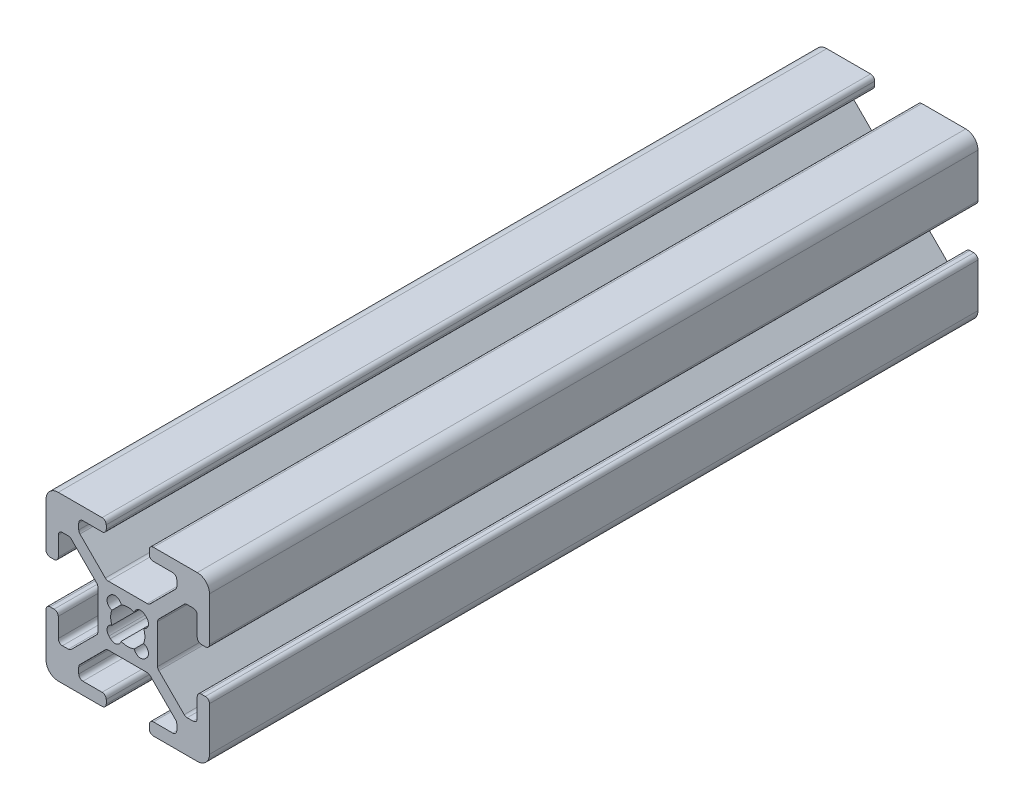
SolidWorks part; units mm, degrees
material "1060 Alloy"
ref_plane "Front Plane" through (0, 0, 0) normal (0, 0, 1) x (1, 0, 0)
ref_plane "Top Plane" through (0, 0, 0) normal (0, 1, 0) x (1, 0, 0)
ref_plane "Right Plane" through (0, 0, 0) normal (1, 0, 0) x (0, 0, -1)
sketch "Sketch2" plane through (0, 0, 0) normal (0, 0, 1) x (1, 0, 0)
  line L0 (-10, -3.138) -> (-10, -8.5)
  line L1 (-8.5, -10) -> (-3.138, -10)
  line L2 (-2.63, -9.492) -> (-2.63, -9.008)
  line L3 (-3.138, -8.5) -> (-5.487, -8.5)
  line L4 (-5.995, -7.992) -> (-5.995, -7.2662)
  line L5 (-5.8462, -6.907) -> (-2.743, -3.8038)
  line L6 (-2.3838, -3.655) -> (2.3841, -3.655)
  line L7 (2.7433, -3.8038) -> (5.8462, -6.9067)
  line L8 (5.995, -7.2659) -> (5.995, -7.992)
  line L9 (5.487, -8.5) -> (3.138, -8.5)
  line L10 (2.63, -9.008) -> (2.63, -9.492)
  line L11 (3.138, -10) -> (8.5, -10)
  line L12 (10, -8.5) -> (10, -3.138)
  line L13 (9.492, -2.63) -> (9.008, -2.63)
  line L14 (8.5, -3.138) -> (8.5, -5.487)
  line L15 (7.992, -5.995) -> (7.2662, -5.995)
  line L16 (6.907, -5.8462) -> (3.8038, -2.743)
  line L17 (3.655, -2.3838) -> (3.655, 2.3841)
  line L18 (3.8038, 2.7433) -> (6.9067, 5.8462)
  line L19 (7.2659, 5.995) -> (7.992, 5.995)
  line L20 (8.5, 5.487) -> (8.5, 3.138)
  line L21 (9.008, 2.63) -> (9.492, 2.63)
  line L22 (10, 3.138) -> (10, 8.5)
  line L23 (8.5, 10) -> (3.138, 10)
  line L24 (2.63, 9.492) -> (2.63, 9.008)
  line L25 (3.138, 8.5) -> (5.487, 8.5)
  line L26 (5.995, 7.992) -> (5.995, 7.2662)
  line L27 (5.8462, 6.907) -> (2.743, 3.8038)
  line L28 (2.3838, 3.655) -> (-2.3841, 3.655)
  line L29 (-2.7433, 3.8038) -> (-5.8462, 6.9067)
  line L30 (-5.995, 7.2659) -> (-5.995, 7.992)
  line L31 (-5.487, 8.5) -> (-3.138, 8.5)
  line L32 (-2.63, 9.008) -> (-2.63, 9.492)
  line L33 (-3.138, 10) -> (-8.5, 10)
  line L34 (-10, 8.5) -> (-10, 3.138)
  line L35 (-9.492, 2.63) -> (-9.008, 2.63)
  line L36 (-8.5, 3.138) -> (-8.5, 5.487)
  line L37 (-7.992, 5.995) -> (-7.2662, 5.995)
  line L38 (-6.907, 5.8462) -> (-3.8038, 2.743)
  line L39 (-3.655, 2.3838) -> (-3.655, -2.3841)
  line L40 (-3.8038, -2.7433) -> (-6.9067, -5.8462)
  line L41 (-7.2659, -5.995) -> (-7.992, -5.995)
  line L42 (-8.5, -5.487) -> (-8.5, -3.138)
  line L43 (-9.008, -2.63) -> (-9.492, -2.63)
  line L44 (-2.1245, 2.3045) -> (-2.3045, 2.1245)
  line L45 (2.3045, 2.1245) -> (2.1245, 2.3045)
  line L46 (2.1245, -2.3045) -> (2.3045, -2.1245)
  line L47 (-2.3045, -2.1245) -> (-2.1245, -2.3045)
  arc A0 (-10, -8.5) -> (-8.5, -10) centre (-8.5, -8.5) ccw
  arc A1 (-3.138, -10) -> (-2.63, -9.492) centre (-3.138, -9.492) ccw
  arc A2 (-2.63, -9.008) -> (-3.138, -8.5) centre (-3.138, -9.008) ccw
  arc A3 (-5.995, -7.992) -> (-5.487, -8.5) centre (-5.487, -7.992) ccw
  arc A4 (-5.8462, -6.907) -> (-5.995, -7.2662) centre (-5.487, -7.2662) ccw
  arc A5 (-2.3838, -3.655) -> (-2.743, -3.8038) centre (-2.3838, -4.163) ccw
  arc A6 (2.7433, -3.8038) -> (2.3841, -3.655) centre (2.3841, -4.163) ccw
  arc A7 (5.995, -7.2659) -> (5.8462, -6.9067) centre (5.487, -7.2659) ccw
  arc A8 (5.487, -8.5) -> (5.995, -7.992) centre (5.487, -7.992) ccw
  arc A9 (3.138, -8.5) -> (2.63, -9.008) centre (3.138, -9.008) ccw
  arc A10 (2.63, -9.492) -> (3.138, -10) centre (3.138, -9.492) ccw
  arc A11 (8.5, -10) -> (10, -8.5) centre (8.5, -8.5) ccw
  arc A12 (10, -3.138) -> (9.492, -2.63) centre (9.492, -3.138) ccw
  arc A13 (9.008, -2.63) -> (8.5, -3.138) centre (9.008, -3.138) ccw
  arc A14 (7.992, -5.995) -> (8.5, -5.487) centre (7.992, -5.487) ccw
  arc A15 (6.907, -5.8462) -> (7.2662, -5.995) centre (7.2662, -5.487) ccw
  arc A16 (3.655, -2.3838) -> (3.8038, -2.743) centre (4.163, -2.3838) ccw
  arc A17 (3.8038, 2.7433) -> (3.655, 2.3841) centre (4.163, 2.3841) ccw
  arc A18 (7.2659, 5.995) -> (6.9067, 5.8462) centre (7.2659, 5.487) ccw
  arc A19 (8.5, 5.487) -> (7.992, 5.995) centre (7.992, 5.487) ccw
  arc A20 (8.5, 3.138) -> (9.008, 2.63) centre (9.008, 3.138) ccw
  arc A21 (9.492, 2.63) -> (10, 3.138) centre (9.492, 3.138) ccw
  arc A22 (10, 8.5) -> (8.5, 10) centre (8.5, 8.5) ccw
  arc A23 (3.138, 10) -> (2.63, 9.492) centre (3.138, 9.492) ccw
  arc A24 (2.63, 9.008) -> (3.138, 8.5) centre (3.138, 9.008) ccw
  arc A25 (5.995, 7.992) -> (5.487, 8.5) centre (5.487, 7.992) ccw
  arc A26 (5.8462, 6.907) -> (5.995, 7.2662) centre (5.487, 7.2662) ccw
  arc A27 (2.3838, 3.655) -> (2.743, 3.8038) centre (2.3838, 4.163) ccw
  arc A28 (-2.7433, 3.8038) -> (-2.3841, 3.655) centre (-2.3841, 4.163) ccw
  arc A29 (-5.995, 7.2659) -> (-5.8462, 6.9067) centre (-5.487, 7.2659) ccw
  arc A30 (-5.487, 8.5) -> (-5.995, 7.992) centre (-5.487, 7.992) ccw
  arc A31 (-3.138, 8.5) -> (-2.63, 9.008) centre (-3.138, 9.008) ccw
  arc A32 (-2.63, 9.492) -> (-3.138, 10) centre (-3.138, 9.492) ccw
  arc A33 (-8.5, 10) -> (-10, 8.5) centre (-8.5, 8.5) ccw
  arc A34 (-10, 3.138) -> (-9.492, 2.63) centre (-9.492, 3.138) ccw
  arc A35 (-9.008, 2.63) -> (-8.5, 3.138) centre (-9.008, 3.138) ccw
  arc A36 (-7.992, 5.995) -> (-8.5, 5.487) centre (-7.992, 5.487) ccw
  arc A37 (-6.907, 5.8462) -> (-7.2662, 5.995) centre (-7.2662, 5.487) ccw
  arc A38 (-3.655, 2.3838) -> (-3.8038, 2.743) centre (-4.163, 2.3838) ccw
  arc A39 (-3.8038, -2.7433) -> (-3.655, -2.3841) centre (-4.163, -2.3841) ccw
  arc A40 (-7.2659, -5.995) -> (-6.9067, -5.8462) centre (-7.2659, -5.487) ccw
  arc A41 (-8.5, -5.487) -> (-7.992, -5.995) centre (-7.992, -5.487) ccw
  arc A42 (-8.5, -3.138) -> (-9.008, -2.63) centre (-9.008, -3.138) ccw
  arc A43 (-9.492, -2.63) -> (-10, -3.138) centre (-9.492, -3.138) ccw
  arc A44 (-1.9358, 0.8037) -> (-1.9358, -0.8037) centre (0, 0) ccw
  arc A45 (-2.3045, 2.1245) -> (-1.9358, 0.8037) centre (-1.748, 1.568) ccw
  arc A46 (-0.8037, 1.9358) -> (-2.1245, 2.3045) centre (-1.568, 1.748) ccw
  arc A47 (0.8037, 1.9358) -> (-0.8037, 1.9358) centre (0, 0) ccw
  arc A48 (2.1245, 2.3045) -> (0.8037, 1.9358) centre (1.568, 1.748) ccw
  arc A49 (1.9358, 0.8037) -> (2.3045, 2.1245) centre (1.748, 1.568) ccw
  arc A50 (1.9358, -0.8037) -> (1.9358, 0.8037) centre (0, 0) ccw
  arc A51 (2.3045, -2.1245) -> (1.9358, -0.8037) centre (1.748, -1.568) ccw
  arc A52 (0.8037, -1.9358) -> (2.1245, -2.3045) centre (1.568, -1.748) ccw
  arc A53 (-0.8037, -1.9358) -> (0.8037, -1.9358) centre (0, 0) ccw
  arc A54 (-2.1245, -2.3045) -> (-0.8037, -1.9358) centre (-1.568, -1.748) ccw
  arc A55 (-1.9358, -0.8037) -> (-2.3045, -2.1245) centre (-1.748, -1.568) ccw
extrude "Boss-Extrude1" add sketch "Sketch2" against normal blind 94
